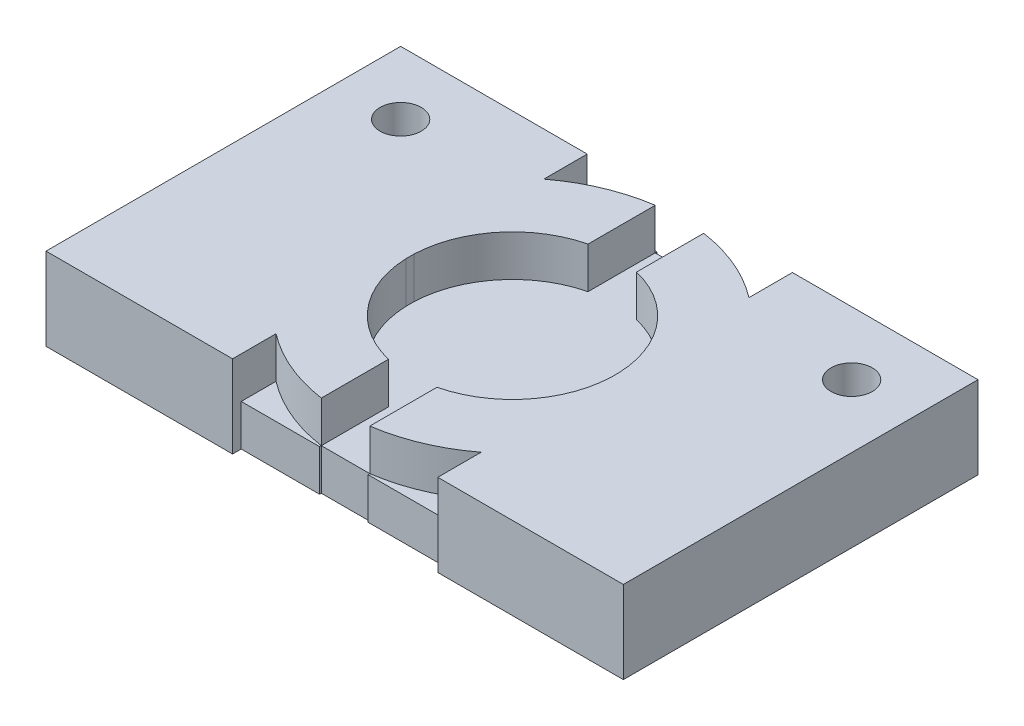
SolidWorks part; units mm, degrees
ref_plane "前基準面" through (0, 0, 0) normal (0, 0, 1) x (1, 0, 0)
ref_plane "上基準面" through (0, 0, 0) normal (0, 1, 0) x (1, 0, 0)
ref_plane "右基準面" through (0, 0, 0) normal (1, 0, 0) x (0, 0, -1)
sketch "草圖1" plane through (0, 0, 0) normal (0, 1, 0) x (1, 0, 0)
  line L1 (-35, 21.5) -> (35, 21.5)
  line L2 (-35, 21.5) -> (-35, -21.5)
  line L3 (-35, -21.5) -> (35, -21.5)
  line L4 (35, 21.5) -> (35, -21.5)
  line L5 (-35, 21.5) -> (35, -21.5) construction
  line L6 (-35, -21.5) -> (35, 21.5) construction
  point P0 (0, 0)
  dimension "D1" = 70
  dimension "D2" = 43
extrude "填料-伸長1" add sketch "草圖1" along normal blind 10
sketch "草圖4" plane through (0, 10, 0) normal (0, 1, 0) x (1, 0, 0)
  line L0 (-35, 21.5) -> (-35, -21.5) construction
  line L1 (35, 21.5) -> (-35, 21.5) construction
  circle A0 centre (-27.34, 13.84) radius 2.5
  dimension "D1" = 5
  dimension "D2" = 7.66
  dimension "D3" = 7.66
extrude "除料-伸長1" cut sketch "草圖4" against normal blind 10
sketch "草圖5" plane through (0, 10, 0) normal (0, 1, 0) x (1, 0, 0)
  line L0 (35, 21.5) -> (-35, 21.5) construction
  line L2 (35, -21.5) -> (35, 21.5) construction
  circle A0 centre (27.34, 13.84) radius 2.5
  dimension "D1" = 7.66
  dimension "D2" = 7.66
  dimension "D3" = 5
extrude "除料-伸長2" cut sketch "草圖5" against normal blind 10
sketch "草圖8" plane through (0, 0, 21.5) normal (0, 0, 1) x (1, 0, 0)
  line L0 (-1035, 5) -> (48965, 5) construction
  line L1 (-35, 10) -> (-35, 0) construction
  line L2 (0, -990) -> (0, 49010) construction
  line L3 (-35, 10) -> (35, 10) construction
  line L4 (35, 10) -> (35, 0) construction
  line L5 (-12.38, 10) -> (12.5, 10)
  line L6 (-12.38, 10) -> (-12.38, 5)
  line L7 (-12.38, 5) -> (12.5, 5)
  line L8 (12.5, 10) -> (12.5, 5)
  point P5 (-35, 5)
  point P10 (0, 10)
  dimension "D1" = 24.88
  dimension "D2" = 22.5
extrude "除料-伸長4" cut sketch "草圖8" against normal through all
sketch "草圖11" plane through (0, 5, 0) normal (0, 1, 0) x (1, 0, 0)
  line L0 (0.06, -978.5) -> (0.06, 49021.5) construction
  line L1 (-12.38, 21.5) -> (12.5, 21.5) construction
  line L2 (-1012.38, 0) -> (48987.62, 0) construction
  line L3 (-12.38, 21.5) -> (-12.38, -21.5) construction
  circle A0 centre (0.06, 0) radius 12.45
  point P5 (0.06, 21.5)
  point P10 (-12.38, 0)
  dimension "D1" = 24.9
extrude "伸長-薄件1" add sketch "草圖11" along normal blind 5 thin
sketch "草圖14" plane through (0, 5, 0) normal (0, 1, 0) x (1, 0, 0)
  line L0 (0.06, -20.45) -> (12.5, -20.45)
  line L1 (12.5, -16.2311) -> (12.5, -21.5) construction
  line L2 (12.5, -20.45) -> (12.5, -21.5)
  line L3 (12.5, -21.5) -> (-12.38, -21.5)
  line L4 (-12.38, -21.5) -> (-12.38, -20.45)
  line L5 (-12.38, -16.2311) -> (-12.38, -21.5) construction
  line L6 (-12.38, -20.45) -> (0.06, -20.45)
  arc A0 (-12.38, -16.2311) -> (12.5, -16.2311) centre (0.06, 0) ccw construction
extrude "除料-伸長6" cut sketch "草圖14" against normal blind 5
sketch "草圖15" plane through (0, 5, 0) normal (0, 1, 0) x (1, 0, 0)
  line L0 (0.06, 20.45) -> (12.5, 20.45)
  line L1 (12.5, 21.5) -> (12.5, 16.2311) construction
  line L2 (12.5, 20.45) -> (12.5, 21.5)
  line L3 (12.5, 21.5) -> (-12.38, 21.5)
  line L4 (-12.38, 21.5) -> (-12.38, 20.45)
  line L5 (-12.38, 21.5) -> (-12.38, 16.2311) construction
  line L6 (-12.38, 20.45) -> (0.06, 20.45)
  arc A0 (12.5, 16.2311) -> (-12.38, 16.2311) centre (0.06, 0) ccw construction
extrude "除料-伸長7" cut sketch "草圖15" against normal blind 5
sketch "草圖16" plane through (0, 10, 0) normal (0, 1, 0) x (1, 0, 0)
  line L0 (0.06, -987.55) -> (0.06, 49012.45) construction
  line L2 (-2.88, 23.0979) -> (3, 23.0979)
  line L3 (-2.88, 23.0979) -> (-2.88, 12.0979)
  line L4 (-2.88, 12.0979) -> (3, 12.0979)
  line L5 (3, 23.0979) -> (3, 12.0979)
  line L6 (-2.88, 23.0979) -> (3, 12.0979) construction
  line L7 (-2.88, 12.0979) -> (3, 23.0979) construction
  arc A0 (12.5, 0.4989) -> (-12.38, 0.4989) centre (0.06, 0) ccw construction
  point P1 (0.06, 17.5979)
  point P6 (0.06, 12.45)
  dimension "D1" = 5.88
  dimension "D2" = 11
extrude "除料-伸長8" cut sketch "草圖16" against normal blind 5
sketch "草圖17" plane through (0, 10, 0) normal (0, 1, 0) x (1, 0, 0)
  line L0 (-2.88, -987.9021) -> (-2.88, 49012.0979) construction
  line L1 (3, -987.9021) -> (3, 49012.0979) construction
  line L2 (12.5, -20.45) -> (0.06, -20.45) construction
  line L3 (-2.88, -12.0979) -> (3, -12.0979)
  line L4 (-2.88, -12.0979) -> (-2.88, -20.45)
  line L5 (-2.88, -20.45) -> (3, -20.45)
  line L6 (3, -12.0979) -> (3, -20.45)
  arc A0 (-12.38, -0.4989) -> (12.5, -0.4989) centre (0.06, 0) ccw construction
extrude "除料-伸長9" cut sketch "草圖17" against normal blind 5
sketch "草圖19" plane through (0, 5, 0) normal (0, 1, 0) x (1, 0, 0)
  line L0 (-2.88, 20.2376) -> (-2.88, 20.45)
  line L1 (-12.38, 20.45) -> (12.5, 20.45) construction
  line L2 (-2.88, 20.45) -> (2.9876, 20.45)
  line L3 (2.9876, 20.45) -> (3, 20.2376)
  line L4 (3, 12.0979) -> (3, 20.2376) construction
  line L5 (3, 20.2376) -> (-2.88, 20.2376)
  arc A0 (12.5, 16.2311) -> (3, 20.2376) centre (0.06, 0) ccw construction
extrude "除料-伸長10" cut sketch "草圖19" against normal blind 5
sketch "草圖20" plane through (0, 5, 0) normal (0, 1, 0) x (1, 0, 0)
  line L0 (3, -20.2376) -> (3, -20.45)
  line L1 (12.5, -20.45) -> (-12.38, -20.45) construction
  line L2 (3, -20.45) -> (-2.8878, -20.45)
  line L3 (-2.8878, -20.45) -> (-2.88, -20.2376)
  line L4 (-2.88, -20.2376) -> (3, -20.2376)
extrude "除料-伸長11" cut sketch "草圖20" against normal blind 5
